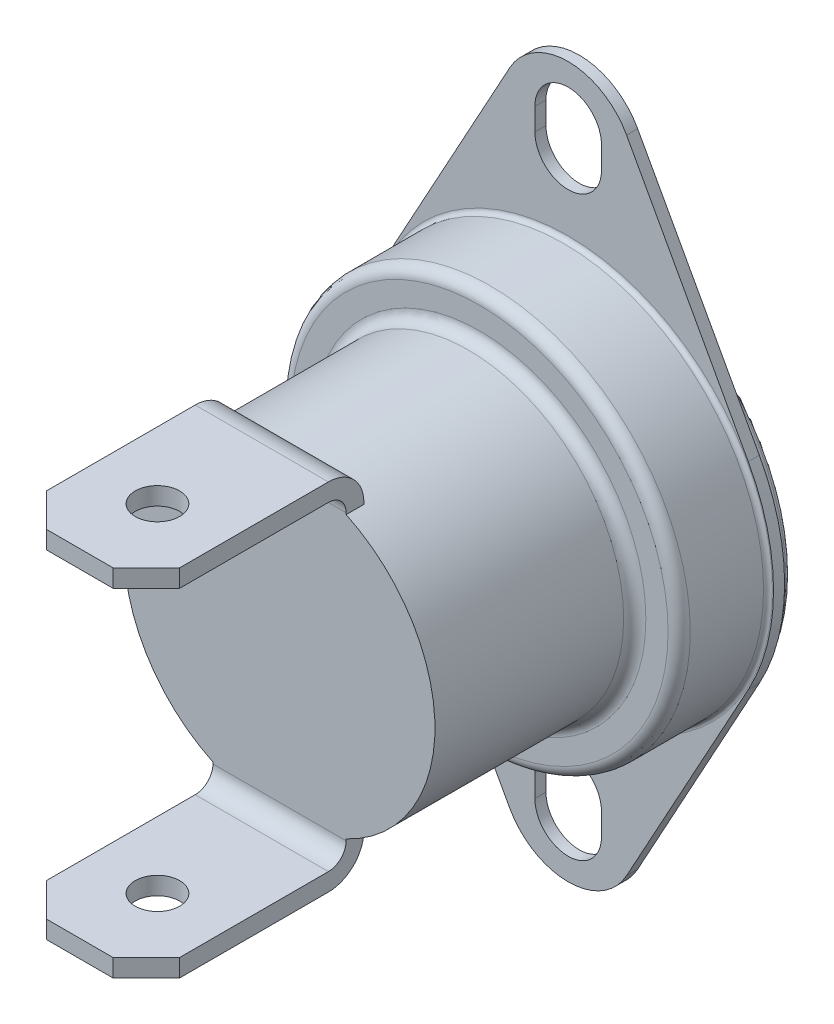
SolidWorks part; units mm, degrees
ref_plane "Спереди" through (0, 0, 0) normal (0, 0, 1) x (1, 0, 0)
ref_plane "Сверху" through (0, 0, 0) normal (0, 1, 0) x (1, 0, 0)
ref_plane "Справа" through (0, 0, 0) normal (1, 0, 0) x (0, 0, -1)
sketch "Эскиз1" plane through (0, 0, 0) normal (0, 0, 1) x (1, 0, 0)
  line L0 (0, 0) -> (0, 44.1509) construction
  line L1 (0, 0) -> (53.3971, 0) construction
  line L2 (-2.6305, 14.4423) -> (-8.1108, 4.4471)
  line L3 (2.6305, 14.4423) -> (8.1108, 4.4471)
  line L4 (2.6305, -14.4423) -> (8.1108, -4.4471)
  line L5 (-2.6305, -14.4423) -> (-8.1108, -4.4471)
  line L6 (1.5, 12.5) -> (1.5, 13.5)
  line L7 (-1.9696, 13) -> (0.8713, 13) construction
  line L8 (-1.5, 12.5) -> (-1.5, 13.5)
  line L9 (1.5, -12.5) -> (1.5, -13.5)
  line L10 (-1.5, -12.5) -> (-1.5, -13.5)
  arc A0 (-8.1108, 4.4471) -> (-8.1108, -4.4471) centre (0, 0) ccw
  arc A1 (2.6305, 14.4423) -> (-2.6305, 14.4423) centre (0, 13) ccw
  arc A2 (2.6305, -14.4423) -> (-2.6305, -14.4423) centre (0, -13) cw
  arc A3 (8.1108, -4.4471) -> (8.1108, 4.4471) centre (0, 0) ccw
  arc A4 (1.5, 13.5) -> (-1.5, 13.5) centre (0, 13.5) ccw
  arc A5 (-1.5, 12.5) -> (1.5, 12.5) centre (0, 12.5) ccw
  arc A6 (1.5, -13.5) -> (-1.5, -13.5) centre (0, -13.5) cw
  arc A7 (-1.5, -12.5) -> (1.5, -12.5) centre (0, -12.5) cw
  dimension "D1" = 18.5
  dimension "D2" = 6
  dimension "D3" = 13
  dimension "D4" = 3
  dimension "D5" = 1
  dimension "D6" = 0.5
extrude "Вытянуть1" add sketch "Эскиз1" along normal blind 0.5
sketch "Эскиз2" plane through (0, 0, 0.5) normal (0, 0, 1) x (1, 0, 0)
  circle A0 centre (0, 0) radius 9
  dimension "D1" = 18
extrude "Вытянуть2" add sketch "Эскиз2" along normal blind 4 and the other way blind 1
sketch "Эскиз3" plane through (0, 0, 4.5) normal (0, 0, 1) x (1, 0, 0)
  circle A0 centre (0, 0) radius 7
  dimension "D1" = 14
extrude "Вытянуть3" add sketch "Эскиз3" along normal offset from surface (9 mm away) 14 up to face at (9, 0, -0.5)
fillet "Скругление1" radius 0.2 2 edges at (-9, 0, 0.5) (9, 0, -0.5)
fillet "Скругление2" radius 0.5 2 edges at (7, 0, 4.5) (9, 0, 4.5)
sketch "Эскиз4" plane through (0, 0, 0) normal (1, 0, 0) x (0, 0, -1)
  line L0 (0, 0) -> (-25.534, 0) construction
  line L1 (-13.5, 7) -> (-13.5, -7) construction
  line L2 (-22.5, 7.2) -> (-14.3, 7.2)
  line L3 (-22.5, 7.2) -> (-22.5, 8)
  line L4 (-22.5, 8) -> (-14.3, 8)
  line L5 (-13.5, -5.1841) -> (-13.5, -6.4)
  line L6 (-12.7, 6.4) -> (-12.7, 5.1841)
  line L7 (-12.7, 5.1841) -> (-13.5, 5.1841)
  line L8 (-13.5, 5.1841) -> (-13.5, 6.4)
  line L9 (-12.7, -5.1841) -> (-13.5, -5.1841)
  line L10 (-12.7, -6.4) -> (-12.7, -5.1841)
  line L11 (-22.5, -8) -> (-14.3, -8)
  line L12 (-22.5, -7.2) -> (-22.5, -8)
  line L13 (-22.5, -7.2) -> (-14.3, -7.2)
  arc A0 (-13.5, 6.4) -> (-14.3, 7.2) centre (-14.3, 6.4) ccw
  arc A1 (-14.3, 8) -> (-12.7, 6.4) centre (-14.3, 6.4) cw
  arc A2 (-14.3, -8) -> (-12.7, -6.4) centre (-14.3, -6.4) ccw
  arc A3 (-13.5, -6.4) -> (-14.3, -7.2) centre (-14.3, -6.4) cw
  dimension "D5" = 0.8
  dimension "D6" = 1.6
  dimension "D1" = 0.8
  dimension "D2" = 8
  dimension "D3" = 9
extrude "Вытянуть4" add sketch "Эскиз4" along normal blind 3 and the other way blind 3
sketch "Эскиз5" plane through (0, -8, 0) normal (0, -1, 0) x (1, 0, 0)
  line L0 (0, 0) -> (0, 20.8922) construction
  line L1 (-3, 22.5) -> (3, 22.5) construction
  circle A0 centre (0, 19) radius 1
  dimension "D2" = 2
  dimension "D1" = 3.5
extrude "Вырез-Вытянуть1" cut sketch "Эскиз5" against normal blind 20
chamfer "Фаска1" distance 1.5 angle 45 4 edges at (-3, 7.6, 22.5) (3, 7.6, 22.5) (3, -7.6, 22.5) (-3, -7.6, 22.5)
